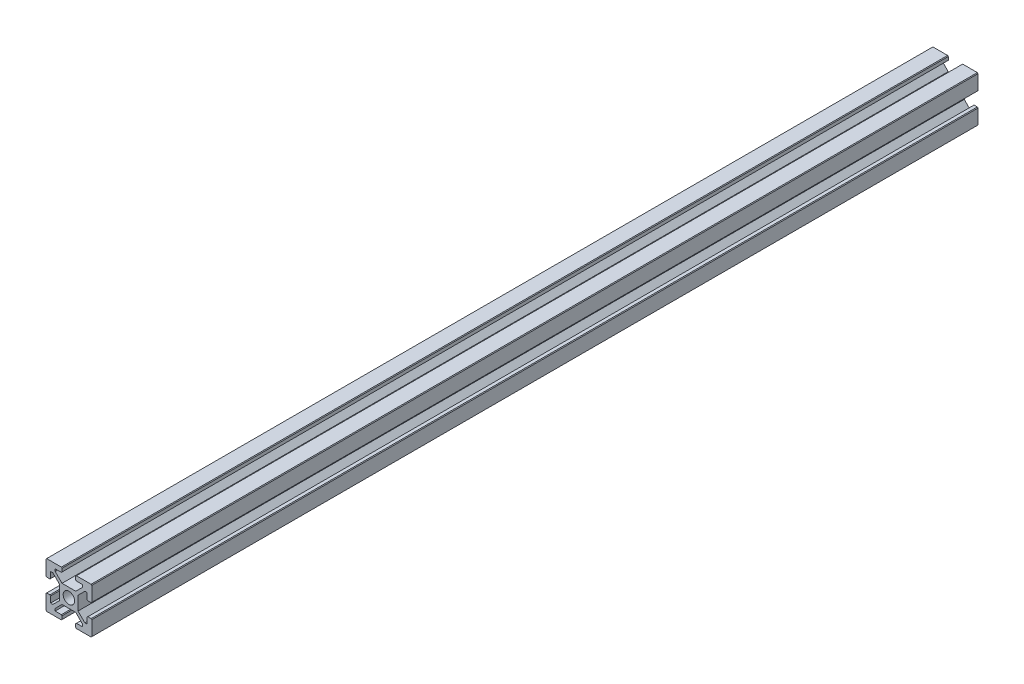
SolidWorks part; units mm, degrees
ref_plane "Front" through (0, 0, 0) normal (0, 0, 1) x (1, 0, 0)
ref_plane "Top" through (0, 0, 0) normal (0, 1, 0) x (1, 0, 0)
ref_plane "Right" through (0, 0, 0) normal (1, 0, 0) x (0, 0, -1)
sketch "Sketch1" plane through (0, 0, 0) normal (0, 0, 1) x (1, 0, 0)
  line L0 (-3, 10) -> (3, 10)
  line L1 (-10, 10) -> (10, 10)
  line L2 (-10, 10) -> (-10, -10)
  line L3 (-10, -10) -> (10, -10)
  line L4 (10, 10) -> (10, -10)
  line L5 (-10, 10) -> (10, -10) construction
  line L6 (-10, -10) -> (10, 10) construction
  line L7 (3, 10) -> (3, 8)
  line L8 (3, 8) -> (6, 8)
  line L9 (-3, 4) -> (3, 4)
  line L10 (0, -55) -> (0, 55) construction
  line L11 (3, 4) -> (6, 7)
  line L12 (6, 7) -> (6, 8)
  line L13 (10, 3) -> (10, -3)
  line L14 (-3, 10) -> (-3, 8)
  line L15 (-3, 8) -> (-6, 8)
  line L16 (-6, 7) -> (-6, 8)
  line L17 (-3, 4) -> (-6, 7)
  line L18 (10, -3) -> (8, -3)
  line L19 (8, -3) -> (8, -6)
  line L20 (7, -6) -> (8, -6)
  line L21 (4, -3) -> (7, -6)
  line L22 (4, 3) -> (4, -3)
  line L23 (4, 3) -> (7, 6)
  line L24 (7, 6) -> (8, 6)
  line L25 (8, 3) -> (8, 6)
  line L26 (10, 3) -> (8, 3)
  line L27 (3, -10) -> (-3, -10)
  line L28 (-3, -10) -> (-3, -8)
  line L29 (-3, -8) -> (-6, -8)
  line L30 (-6, -7) -> (-6, -8)
  line L31 (-3, -4) -> (-6, -7)
  line L32 (3, -4) -> (-3, -4)
  line L33 (3, -4) -> (6, -7)
  line L34 (6, -7) -> (6, -8)
  line L35 (3, -8) -> (6, -8)
  line L36 (3, -10) -> (3, -8)
  line L37 (-10, -3) -> (-10, 3)
  line L38 (-10, 3) -> (-8, 3)
  line L39 (-8, 3) -> (-8, 6)
  line L40 (-7, 6) -> (-8, 6)
  line L41 (-4, 3) -> (-7, 6)
  line L42 (-4, -3) -> (-4, 3)
  line L43 (-4, -3) -> (-7, -6)
  line L44 (-7, -6) -> (-8, -6)
  line L45 (-8, -3) -> (-8, -6)
  line L46 (-10, -3) -> (-8, -3)
  circle A0 centre (0, 0) radius 2.5
  point P0 (0, 0)
  point P18 (0, 10)
  point P22 (0, 4)
  point P53 (0, 0)
  dimension "D9" = 5
  dimension "D1" = 20
  dimension "D2" = 20
  dimension "D3" = 3
  dimension "D4" = 2
  dimension "D5" = 3
  dimension "D6" = 6
  dimension "D7" = 3
  dimension "D8" = 4
extrude "Boss-Extrude1" add sketch "Sketch1" along normal blind 387.35 contours L46 L2 L3 L28 L29 L30 L31 L32 L33 L34 L35 L36 L4 L18 L19 L20 L21 L22 L23 L24 L25 L26 L1 L7 L8 L12 L11 L9 L17 L16 L15 L14 L38 L39 L40 L41 L42 L43 L44 L45 A0
chamfer "Chamfer1" distance 0.2828 angle 45 20 edges at (-8, 3, 193.675) (-3, 8, 193.675) (-3, 10, 193.675) (-10, 3, 193.675) (-10, 10, 193.675) (-8, -3, 193.675) (-10, -3, 193.675) (-10, -10, 193.675) (-3, -10, 193.675) (-3, -8, 193.675) (3, -8, 193.675) (3, -10, 193.675) (8, -3, 193.675) (10, -10, 193.675) (10, -3, 193.675) (8, 3, 193.675) (10, 3, 193.675) (10, 10, 193.675) (3, 8, 193.675) (3, 10, 193.675)
